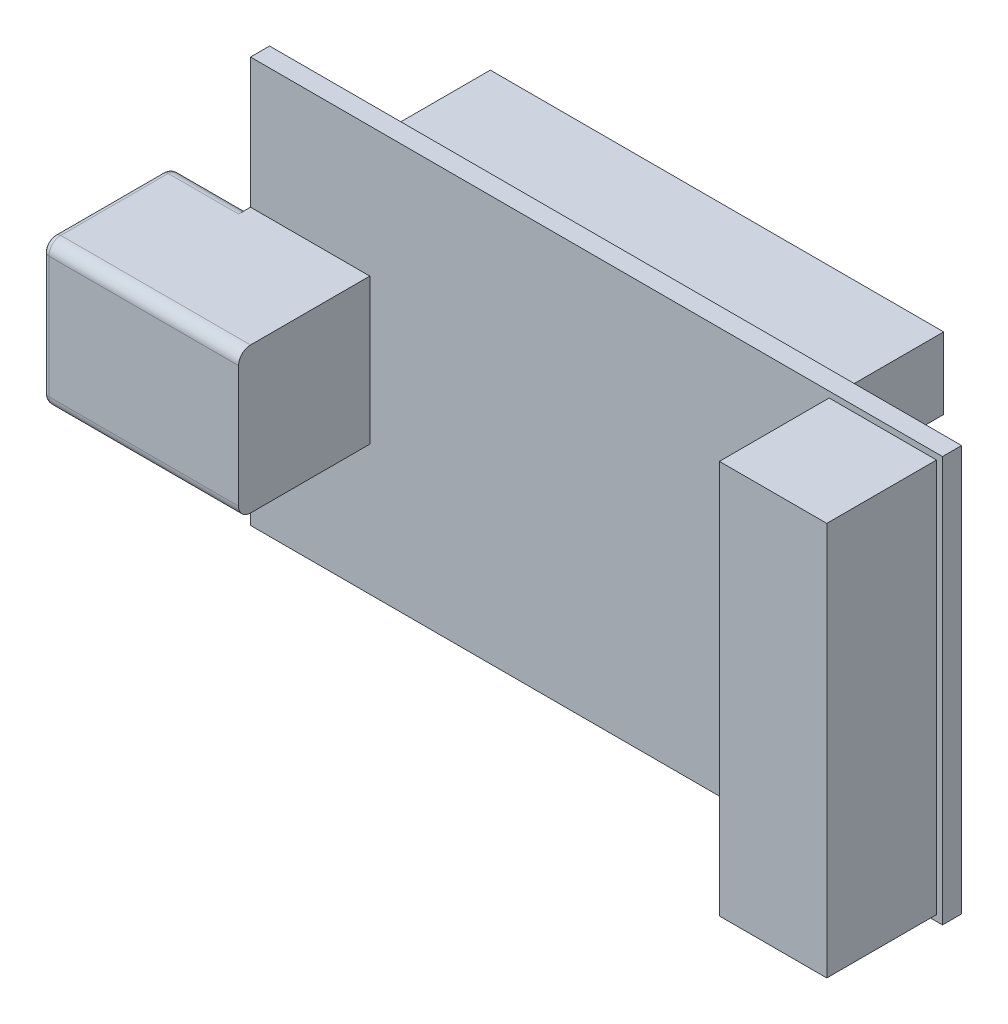
SolidWorks part; units mm, degrees
ref_plane "Front Plane" through (0, 0, 0) normal (0, 0, 1) x (1, 0, 0)
ref_plane "Top Plane" through (0, 0, 0) normal (0, 1, 0) x (1, 0, 0)
ref_plane "Right Plane" through (0, 0, 0) normal (1, 0, 0) x (0, 0, -1)
sketch "Sketch1" plane through (0, 0, 0) normal (0, 0, 1) x (1, 0, 0)
  line L1 (0, 0) -> (58, 0)
  line L2 (0, 0) -> (0, 34)
  line L3 (0, 34) -> (58, 34)
  line L4 (58, 0) -> (58, 34)
  dimension "D1" = 34
  dimension "D2" = 58
extrude "Extrude1" add sketch "Sketch1" along normal blind 1.6
sketch "Sketch2" plane through (0, 0, 0) normal (0, 0, -1) x (-1, 0, 0)
  line L0 (0, 34) -> (0, 0) construction
  line L1 (-10, 33) -> (-48, 33)
  line L2 (-10, 33) -> (-10, 27)
  line L3 (-10, 27) -> (-48, 27)
  line L4 (-48, 33) -> (-48, 27)
  line L5 (-58, 34) -> (0, 34) construction
  line L6 (0, 17) -> (-58, 17) construction
  line L7 (-58, 0) -> (-58, 34) construction
  line L8 (-48, 1) -> (-48, 7)
  line L9 (-10, 7) -> (-48, 7)
  line L10 (-10, 1) -> (-10, 7)
  line L11 (-10, 1) -> (-48, 1)
  dimension "D1" = 38
  dimension "D2" = 6
  dimension "D3" = 10
  dimension "D4" = 1
extrude "Extrude2" add sketch "Sketch2" along normal blind 8.5
sketch "Sketch3" plane through (0, 0, 1.6) normal (0, 0, 1) x (1, 0, 0)
  line L0 (58, 17) -> (0, 17) construction
  line L1 (58, 0) -> (58, 34) construction
  line L2 (0, 34) -> (0, 0) construction
  line L3 (0, 0) -> (58, 0) construction
  line L4 (57.5, 33.5) -> (48.5, 33.5)
  line L5 (57.5, 33.5) -> (57.5, 0.5)
  line L6 (57.5, 0.5) -> (48.5, 0.5)
  line L7 (48.5, 33.5) -> (48.5, 0.5)
  dimension "D1" = 9
  dimension "D2" = 9.5
  dimension "D3" = 33
  dimension "D4" = 0.5
extrude "Extrude3" add sketch "Sketch3" along normal blind 9.2
sketch "Sketch4" plane through (0, 0, 1.6) normal (0, 0, 1) x (1, 0, 0)
  line L0 (0, 34) -> (0, 0) construction
  line L1 (10, 10.9) -> (-6.4, 10.9)
  line L2 (10, 10.9) -> (10, 23.1)
  line L3 (10, 23.1) -> (-6.4, 23.1)
  line L4 (-6.4, 10.9) -> (-6.4, 23.1)
  line L5 (0, 0) -> (58, 0) construction
  dimension "D1" = 16.4
  dimension "D2" = 10
  dimension "D3" = 12.2
  dimension "D4" = 10.9
extrude "Extrude4" add sketch "Sketch4" along normal blind 11
sketch "Sketch5" plane through (-6.4, 0, 0) normal (-1, 0, 0) x (0, 0, 1)
  line L7 (8.8, 21.3) -> (10.8, 19.3)
  line L8 (12.6, 17) -> (1.6, 17) construction
  line L9 (12.6, 23.1) -> (12.6, 10.9) construction
  line L10 (1.6, 23.1) -> (1.6, 10.9) construction
  line L11 (3.4, 21.3) -> (3.4, 12.7)
  line L12 (3.4, 12.7) -> (10.8, 12.7)
  line L13 (10.8, 12.7) -> (10.8, 21.3)
  line L14 (10.8, 21.3) -> (3.4, 21.3)
  line L15 (3.4, 21.3) -> (3.4, 12.7)
  line L16 (3.4, 12.7) -> (8.8, 12.7)
  line L17 (10.8, 14.7) -> (10.8, 19.3)
  line L18 (8.8, 21.3) -> (3.4, 21.3)
  line L19 (8.8, 12.7) -> (10.8, 14.7)
  dimension "D1" = 1.8
  dimension "D2" = 2
  dimension "D3" = 2
extrude "Cut-Extrude1" cut sketch "Sketch5" against normal blind 14
fillet "Fillet1" radius 1 4 edges at (1.8, 10.9, 12.6) (-3.2, 10.9, 1.6) (-3.2, 23.1, 1.6) (1.8, 23.1, 12.6)
fillet "Fillet2" radius 0.5 14 edges at (-6.4, 11.1929, 1.8929) (-6.4, 17, 1.6) (-6.4, 22.8071, 1.8929) (-6.4, 23.1, 7.1) (-6.4, 22.8071, 12.3071) (-6.4, 17, 12.6) (-6.4, 11.1929, 12.3071) (-6.4, 10.9, 7.1) (-6.4, 12.7, 6.1) (-6.4, 13.7, 9.8) (-6.4, 17, 10.8) (-6.4, 20.3, 9.8) (-6.4, 21.3, 6.1) (-6.4, 17, 3.4)
